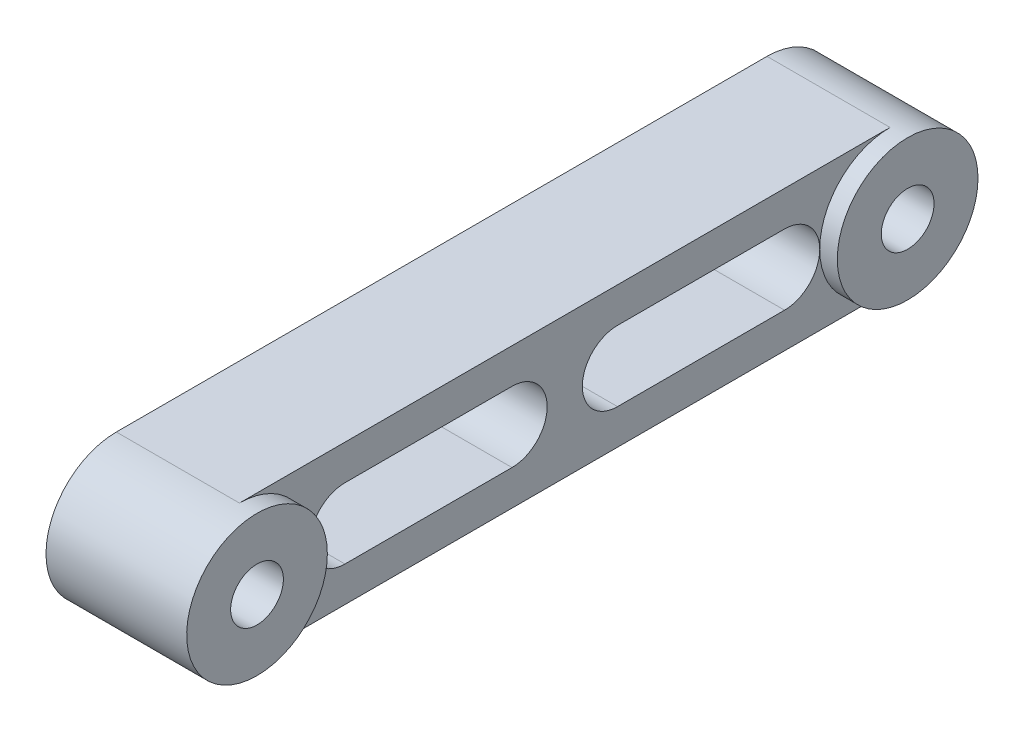
SolidWorks part; units mm, degrees
ref_plane "前视基准面" through (0, 0, 0) normal (0, 0, 1) x (1, 0, 0)
ref_plane "上视基准面" through (0, 0, 0) normal (0, 1, 0) x (1, 0, 0)
ref_plane "右视基准面" through (0, 0, 0) normal (1, 0, 0) x (0, 0, -1)
sketch "草图2" plane through (0, 0, 0) normal (1, 0, 0) x (0, 0, -1)
  line L0 (0, 0) -> (37, 0) construction
  line L1 (0, 0) -> (37, 0) construction
  line L2 (0, 4) -> (37, 4)
  line L3 (0, -4) -> (37, -4)
  circle A0 centre (0, 0) radius 1.5
  circle A1 centre (37, 0) radius 1.5
  arc A2 (0, 4) -> (0, -4) centre (0, 0) ccw
  arc A3 (37, -4) -> (37, 4) centre (37, 0) ccw
  point P5 (18.5, 0)
  dimension "D2" = 3
  dimension "D3" = 4
  dimension "D1" = 37
extrude "凸台-拉伸1" add sketch "草图2" along normal blind 7
sketch "草图3" plane through (7, 0, 0) normal (1, 0, 0) x (0, 0, -1)
  line L0 (0, 0) -> (18.5, 0) construction
  line L1 (18.5, 0) -> (18.5, 4) construction
  line L2 (37, 4) -> (0, 4) construction
  line L3 (15.5, 0) -> (6, 0) construction
  line L4 (15.5, -2) -> (6, -2)
  line L5 (15.5, 2) -> (6, 2)
  line L6 (21.5, 0) -> (31, 0) construction
  line L7 (21.5, -2) -> (31, -2)
  line L8 (21.5, 2) -> (31, 2)
  arc A0 (15.5, -2) -> (15.5, 2) centre (15.5, 0) ccw
  arc A1 (6, 2) -> (6, -2) centre (6, 0) ccw
  circle A2 centre (0, 0) radius 1.5 construction
  arc A3 (21.5, -2) -> (21.5, 2) centre (21.5, 0) cw
  arc A4 (31, 2) -> (31, -2) centre (31, 0) cw
  point P8 (10.75, 0)
  point P18 (26.25, 0)
  dimension "D1" = 2
  dimension "D2" = 6
  dimension "D3" = 6
extrude "切除-拉伸1" cut sketch "草图3" against normal blind 5
sketch "草图4" plane through (7, 0, 0) normal (1, 0, 0) x (0, 0, -1)
  circle A0 centre (0, 0) radius 4
  circle A1 centre (37, 0) radius 4
  arc A2 (37, -4) -> (37, 4) centre (37, 0) ccw construction
  arc A3 (37, -4) -> (37, 4) centre (37, 0) ccw
  circle A4 centre (37, 0) radius 1.5 construction
  circle A5 centre (0, 0) radius 1.5 construction
  circle A6 centre (37, 0) radius 1.5
  circle A7 centre (0, 0) radius 1.5
  circle M11 centre (0, 0) radius 1.5
  arc M12 (0, 4) -> (0, -4) centre (0, 0) ccw
  arc M14 (37, -4) -> (37, 4) centre (37, 0) ccw
  circle M16 centre (37, 0) radius 1.5
extrude "凸台-拉伸2" add sketch "草图4" along normal blind 1 contours A1 M14 M16 | A0 M12 M11
